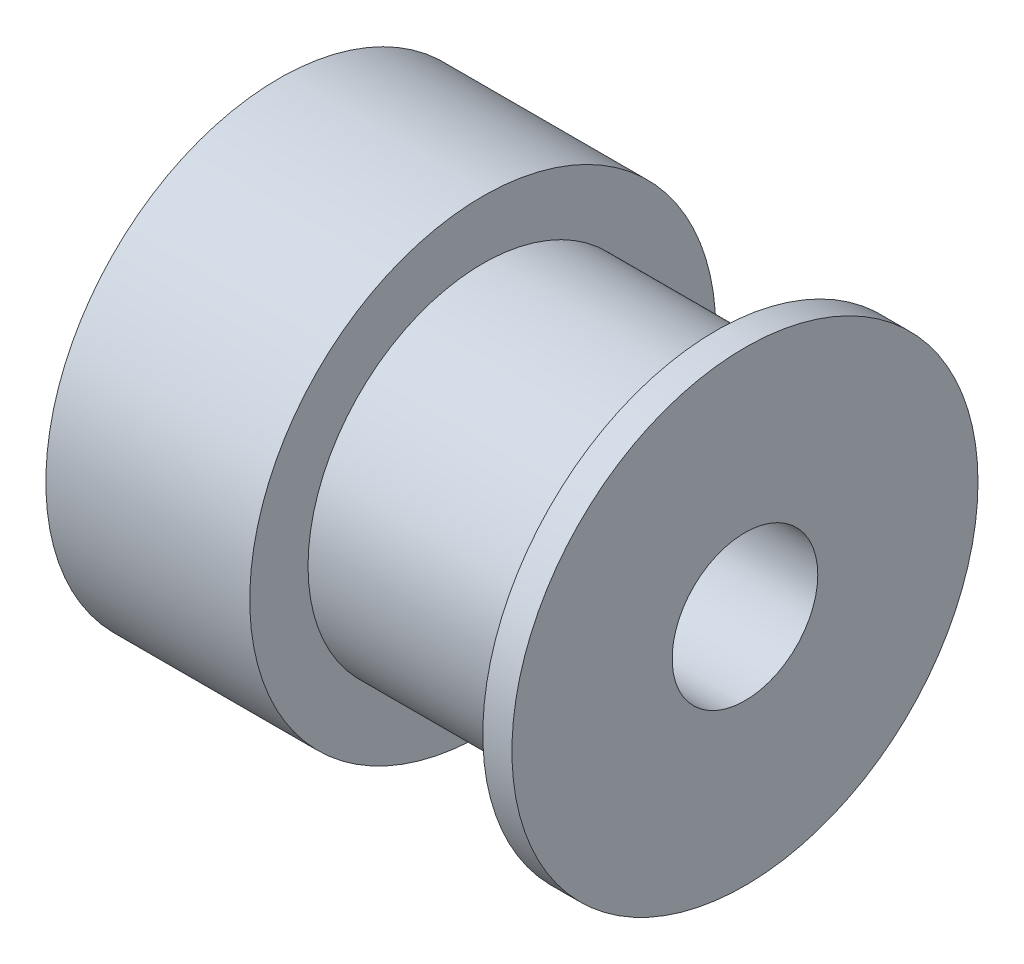
SolidWorks part; units mm, degrees
ref_plane "前基準面" through (0, 0, 0) normal (0, 0, 1) x (1, 0, 0)
ref_plane "上基準面" through (0, 0, 0) normal (0, 1, 0) x (1, 0, 0)
ref_plane "右基準面" through (0, 0, 0) normal (1, 0, 0) x (0, 0, -1)
sketch "草圖1" plane through (0, 0, 0) normal (0, 0, 1) x (1, 0, 0)
  line L0 (0, 2.5) -> (-16, 2.5)
  line L1 (-16, 2.5) -> (-16, 8)
  line L2 (-16, 8) -> (-9, 8)
  line L3 (-9, 8) -> (-9, 6)
  line L4 (-9, 6) -> (-1, 6)
  line L5 (-1, 6) -> (-1, 8)
  line L6 (-1, 8) -> (0, 8)
  line L7 (0, 8) -> (0, 2.5)
  line L8 (0, 0) -> (-16, 0) construction
  point P11 (0, 0)
  dimension "D1" = 16
  dimension "D2" = 2.5
  dimension "D3" = 1
  dimension "D4" = 7
  dimension "D5" = 8
  dimension "D6" = 8
  dimension "D7" = 6
revolve "旋轉1" add sketch "草圖1" angle 360 about L8
